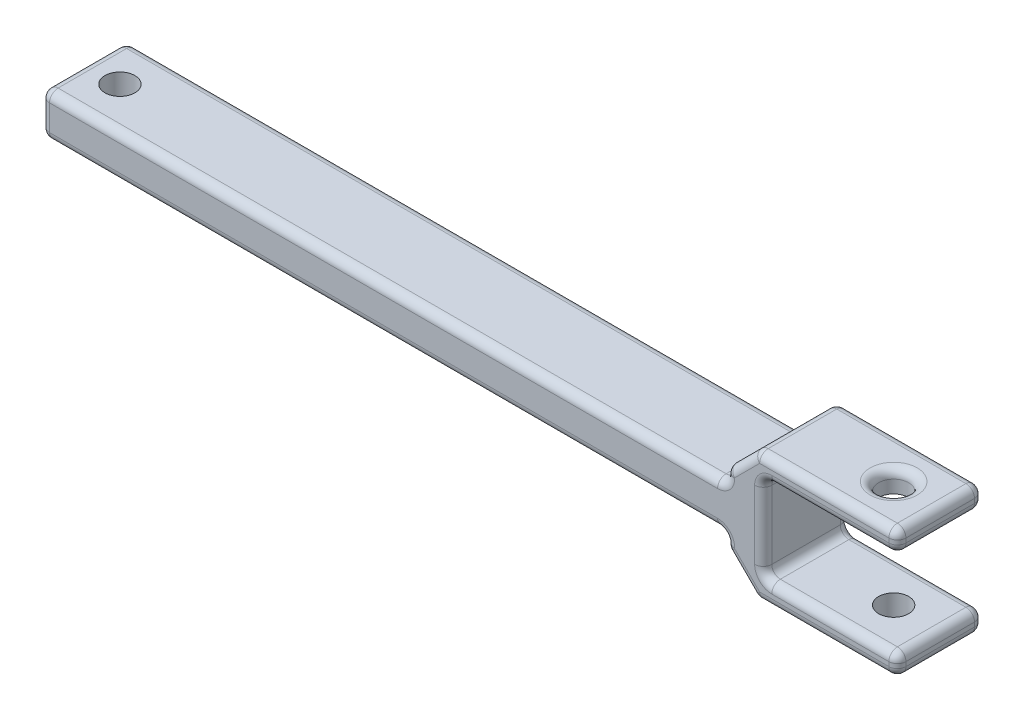
SolidWorks part; units mm, degrees
ref_plane "Front Plane" through (0, 0, 0) normal (0, 0, 1) x (1, 0, 0)
ref_plane "Top Plane" through (0, 0, 0) normal (0, 1, 0) x (1, 0, 0)
ref_plane "Right Plane" through (0, 0, 0) normal (1, 0, 0) x (0, 0, -1)
sketch "Sketch1" plane through (0, 0, 0) normal (0, 0, 1) x (1, 0, 0)
  line L0 (0, 0) -> (97.6775, 0) construction
  line L1 (46.3083, 32.1208) -> (46.3083, -27.483) construction
  line L15 (20.116, 2.5) -> (100.116, 2.5)
  line L16 (100.116, 2.5) -> (100.116, 7.5)
  line L17 (100.116, 7.5) -> (120.116, 7.5)
  line L18 (120.116, 7.5) -> (120.116, -7.5)
  line L19 (120.116, -7.5) -> (100.116, -7.5)
  line L20 (100.116, -7.5) -> (100.116, -2.5)
  line L21 (100.116, -2.5) -> (20.116, -2.5)
  line L22 (20.116, -2.5) -> (20.116, 2.5)
  dimension "D1" = 7.5
  dimension "D2" = 2.5
  dimension "D3" = 5
  dimension "D4" = 15
  dimension "D5" = 100
  dimension "D6" = 20
extrude "Boss-Extrude1" add sketch "Sketch1" against normal blind 10
sketch "Sketch4" plane through (0, 0, 0) normal (0, 0, 1) x (1, 0, 0)
  line L0 (120.116, -7.5) -> (120.116, 7.5) construction
  line L1 (120.116, 5) -> (104.4476, 5)
  line L2 (120.116, 5) -> (120.116, -5)
  line L3 (120.116, -5) -> (104.4476, -5)
  line L4 (104.4476, 5) -> (104.4476, -5)
  dimension "D1" = 5
  dimension "D2" = 10
extrude "Cut-Extrude2" cut sketch "Sketch4" against normal through all
chamfer "Chamfer2" distance 3.5 angle 45 2 edges at (100.116, -7.5, -5) (100.116, 7.5, -5)
fillet "Fillet3" radius 1 42 edges at (20.116, -2.5, -5) (100.116, -2.5, -5) (100.116, -4, -5) (103.616, -7.5, -5) (120.116, -7.5, -5) (120.116, -6.25, -10) (100.116, 3.25, -10) (20.116, 0, -10) (60.116, -2.5, -10) (100.116, -3.25, -10) (101.866, -5.75, -10) (111.866, -7.5, -10) (120.116, 6.25, -10) (120.116, 5, -5) (112.2818, 5, -10) (104.4476, 5, -5) (104.4476, 0, -10) (104.4476, -5, -5) (112.2818, -5, -10) (120.116, -5, -5) (100.116, 4, -5) (101.866, 5.75, -10) (120.116, 7.5, -5) (103.616, 7.5, -5) (111.866, 7.5, -10) (60.116, -2.5, 0) (20.116, 0, 0) (100.116, 3.25, 0) (101.866, 5.75, 0) (111.866, 7.5, 0) (120.116, 6.25, 0) (112.2818, 5, 0) (104.4476, 0, 0) (112.2818, -5, 0) (120.116, -6.25, 0) (111.866, -7.5, 0) (101.866, -5.75, 0) (100.116, -3.25, 0) (20.116, 2.5, -5) (60.116, 2.5, -10) (100.116, 2.5, -5) (60.116, 2.5, 0)
sketch "Sketch6" plane through (0, 7.5, 0) normal (0, 1, 0) x (1, 0, 0)
  line L1 (104.0303, 1) -> (119.116, 1) construction
  circle A0 centre (114.6801, 5) radius 1.75
  dimension "D2" = 3.5
  dimension "D1" = 4
extrude "Cut-Extrude3" cut sketch "Sketch6" against normal through all
sketch "Sketch9" plane through (0, 2.5, 0) normal (0, 1, 0) x (1, 0, 0)
  line L0 (21.116, 1) -> (99.116, 1) construction
  circle A0 centre (24.3368, 5) radius 1.75
  dimension "D2" = 3.5
  dimension "D1" = 4
extrude "Cut-Extrude4" cut sketch "Sketch9" against normal through all
fillet "Fillet1" radius 1 1 edges at (112.9301, 7.5, -5)
